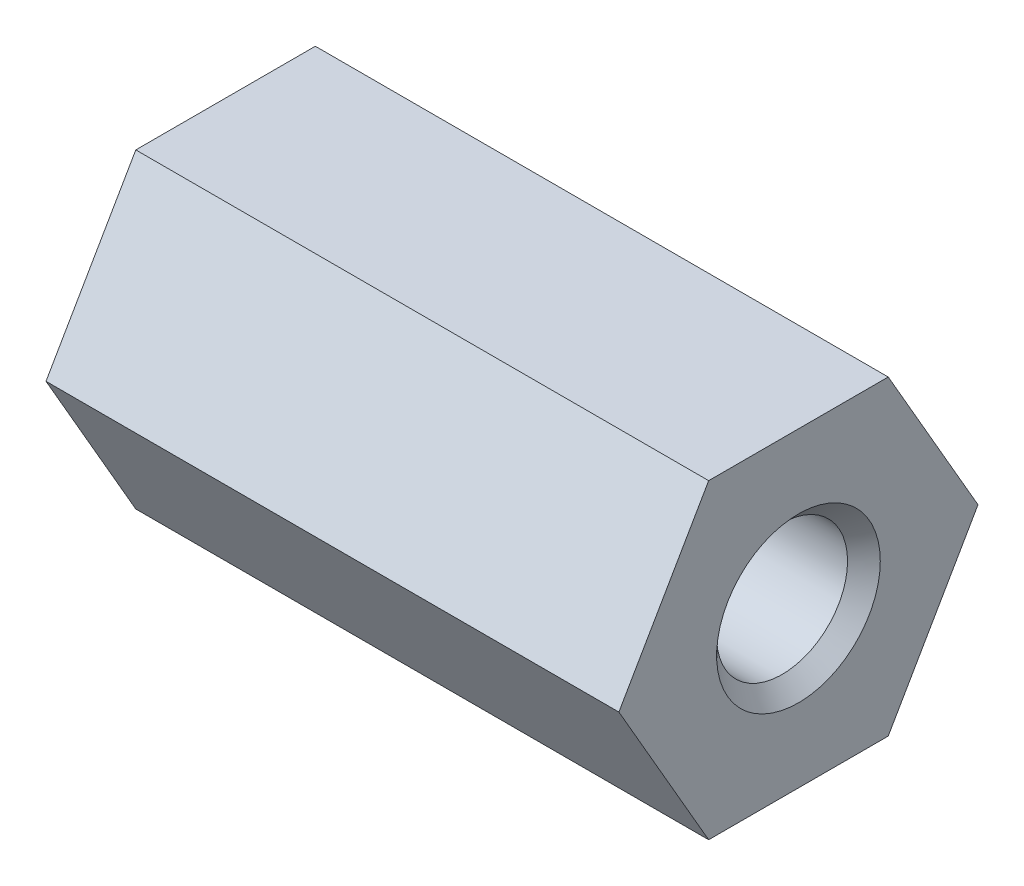
SolidWorks part; units mm, degrees
ref_plane "Спереди" through (0, 0, 0) normal (0, 0, 1) x (1, 0, 0)
ref_plane "Сверху" through (0, 0, 0) normal (0, 1, 0) x (1, 0, 0)
ref_plane "Справа" through (0, 0, 0) normal (1, 0, 0) x (0, 0, -1)
sketch "Эскиз2" plane through (0, 0, 0) normal (1, 0, 0) x (0, 0, -1)
  line L0 (-5.4848, 9.5) -> (5.4848, 9.5)
  line L1 (5.4848, 9.5) -> (10.9697, 0)
  line L2 (10.9697, 0) -> (5.4848, -9.5)
  line L3 (5.4848, -9.5) -> (-5.4848, -9.5)
  line L4 (-5.4848, -9.5) -> (-10.9697, 0)
  line L5 (-10.9697, 0) -> (-5.4848, 9.5)
  circle A0 centre (0, 0) radius 10.9697
  circle A1 centre (0, 0) radius 4
  dimension "D2" = 8
  dimension "D1" = 19
extrude "Бобышка-Вытянуть1" add sketch "Эскиз2" along normal blind 35 contours L5 L4 L3 L2 L1 L0 A1
chamfer "Фаска1" distance 1 angle 45 2 edges at (0, 0, -4) (35, 0, -4)
ref_plane "Плоскость1" through (35, 0, 0) normal (1, 0, 0) x (0, 0, -1)
sketch "Эскиз3" plane through (35, 0, 0) normal (1, 0, 0) x (0, 0, -1)
  line L0 (-3.0599, 20.3784) -> (7.2606, 20.3784)
  line L1 (7.2606, 20.3784) -> (7.2606, 9.5)
  line L2 (7.2606, 9.5) -> (-3.0599, 9.5)
  line L3 (-3.0599, 9.5) -> (-3.0599, 20.3784)
  line L4 (15.2967, 14.0646) -> (8.0721, 2.1849)
  line L5 (8.0721, 2.1849) -> (9.1892, 1.5056)
  line L6 (9.1892, 1.5056) -> (16.4901, 13.5107)
  line L7 (16.4901, 13.5107) -> (15.2967, 14.0646)
  line L8 (-5.4848, 9.5) -> (5.4848, 9.5) construction
  point P7 (0, 0)
  point P11 (0, 0)
  point P12 (7.2606, 20.3784)
